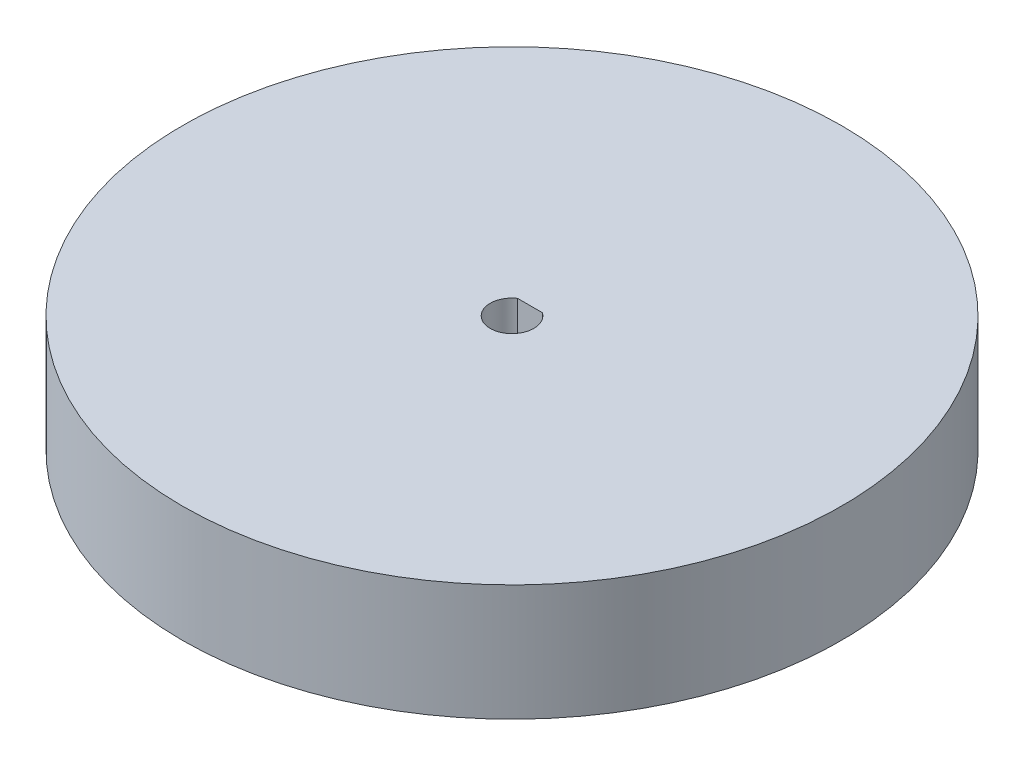
SolidWorks part; units mm, degrees
ref_plane "Front Plane" through (0, 0, 0) normal (0, 0, 1) x (1, 0, 0)
ref_plane "Top Plane" through (0, 0, 0) normal (0, 1, 0) x (1, 0, 0)
ref_plane "Right Plane" through (0, 0, 0) normal (1, 0, 0) x (0, 0, -1)
sketch "Sketch2" plane through (0, 0, 0) normal (0, 1, 0) x (1, 0, 0)
  circle A0 centre (0, 0) radius 43.18
  dimension "D1" = 86.36
extrude "Boss-Extrude1" add sketch "Sketch2" along normal blind 15.24
sketch "Sketch3" plane through (0, 15.24, 0) normal (0, 1, 0) x (1, 0, 0)
  line L0 (-1.6264, 2.3495) -> (1.6264, 2.3495)
  circle A0 centre (0, 0) radius 2.8575
  point P5 (0, -2.8575)
  dimension "D1" = 5.715
  dimension "D2" = 5.207
extrude "Cut-Extrude1" cut sketch "Sketch3" against normal through all contours L0 A0
equation "\"MDF\"= .3"
equation "\"Foamcore\"= .1"
equation "\"GMaterial\"= .6"
equation "\"CutDistance\" = .1"
equation "\"D1@Boss-Extrude1\"=\"GMaterial\""
